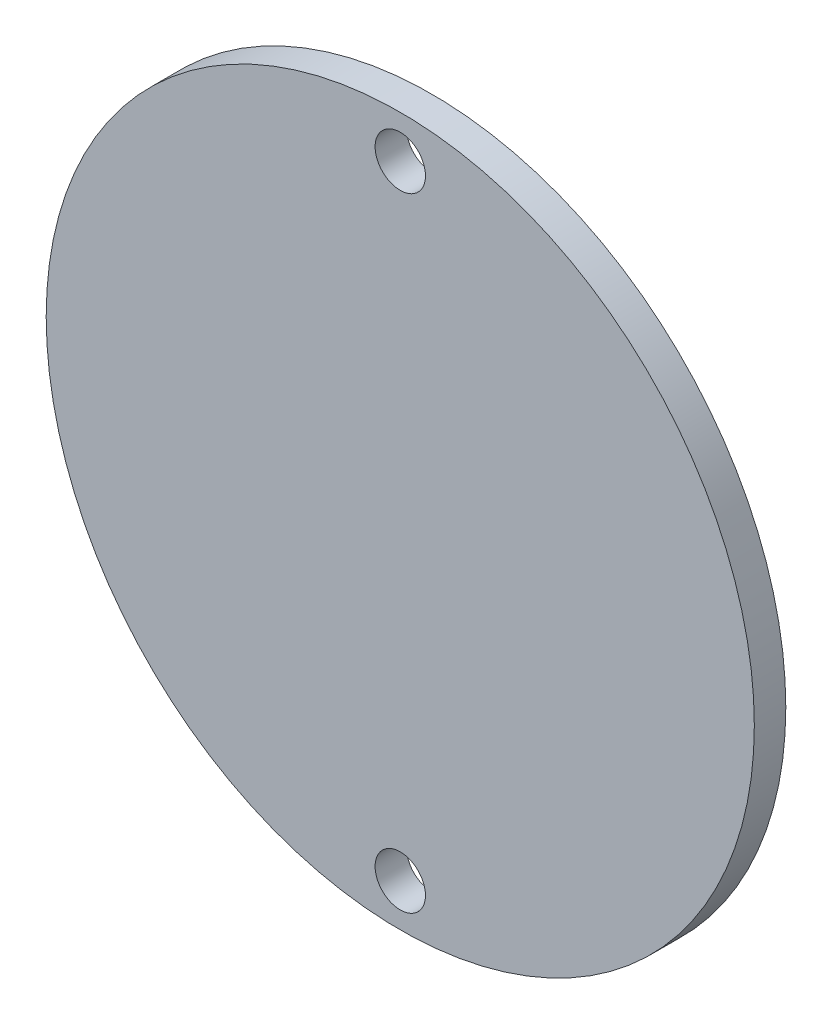
SolidWorks part; units mm, degrees
ref_plane "前视基准面" through (0, 0, 0) normal (0, 0, 1) x (1, 0, 0)
ref_plane "上视基准面" through (0, 0, 0) normal (0, 1, 0) x (1, 0, 0)
ref_plane "右视基准面" through (0, 0, 0) normal (1, 0, 0) x (0, 0, -1)
other "Configuration Table"
sketch "草图1" plane through (0, 0, 0) normal (0, 0, 1) x (1, 0, 0)
  line L0 (0, 24.4681) -> (0, -25.6239) construction
  circle A0 centre (0, 0) radius 22.5
  circle A1 centre (0, 0) radius 19.8 construction
  circle A2 centre (0, 19.8) radius 1.6
  circle A3 centre (0, -19.8) radius 1.6
  dimension "D1" = 45
  dimension "D2" = 39.6
extrude "凸台-拉伸1" add sketch "草图1" along normal blind 2
sketch "草图2" plane through (0, 0, 2) normal (0, 0, 1) x (1, 0, 0)
  line L0 (0, 0) -> (20.2555, 20.2555) construction
  line L1 (0, 0) -> (0, 24.653) construction
  circle A0 centre (0, 0) radius 12.5 construction
  circle A1 centre (8.8388, 8.8388) radius 1.6
  circle A2 centre (3.2352, -12.0741) radius 1.6
  circle A3 centre (-12.0741, 3.2352) radius 1.6
  point P13 (0, 0)
  dimension "D1" = 45
  dimension "D2" = 3
